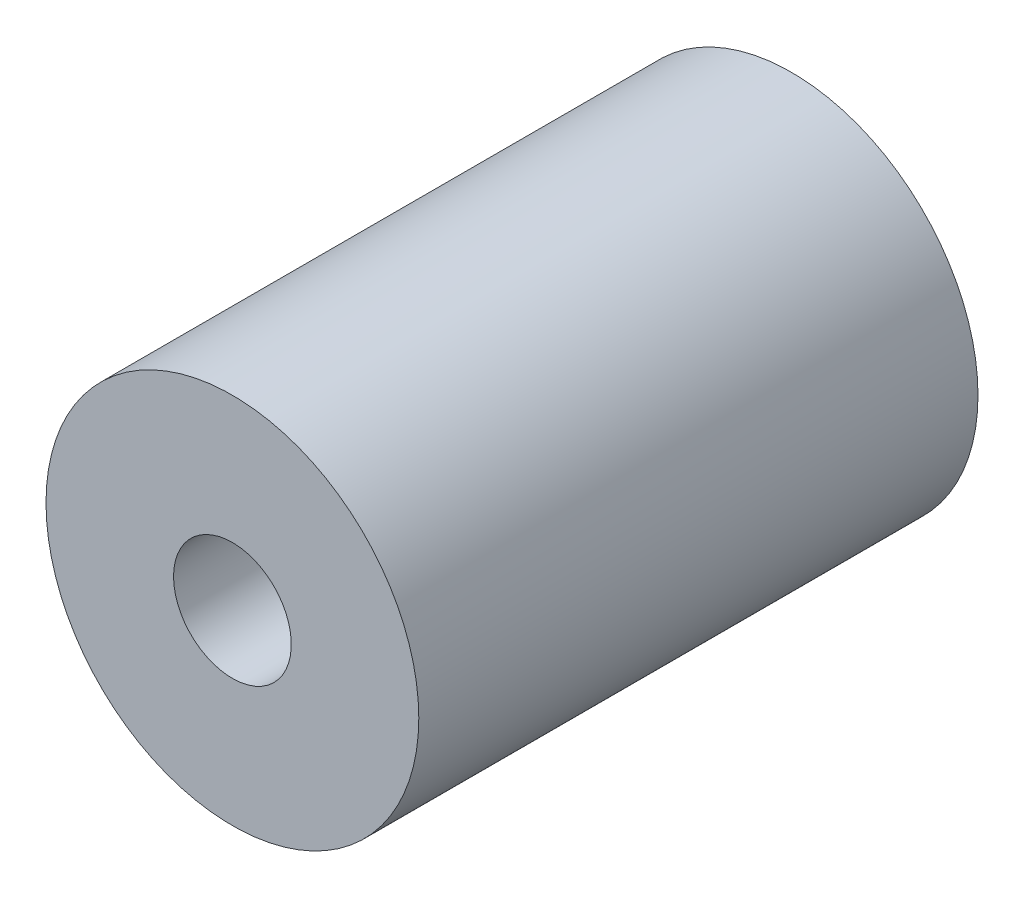
SolidWorks part; units mm, degrees
material "1060 Alloy"
ref_plane "Front Plane" through (0, 0, 0) normal (0, 0, 1) x (1, 0, 0)
ref_plane "Top Plane" through (0, 0, 0) normal (0, 1, 0) x (1, 0, 0)
ref_plane "Right Plane" through (0, 0, 0) normal (1, 0, 0) x (0, 0, -1)
sketch "Sketch1" plane through (0, 0, 0) normal (0, 0, 1) x (1, 0, 0)
  circle A0 centre (0, 0) radius 6
  circle A1 centre (0, 0) radius 19
  dimension "D1" = 12
  dimension "D2" = 38
extrude "Boss-Extrude1" add sketch "Sketch1" along normal mid plane 57
